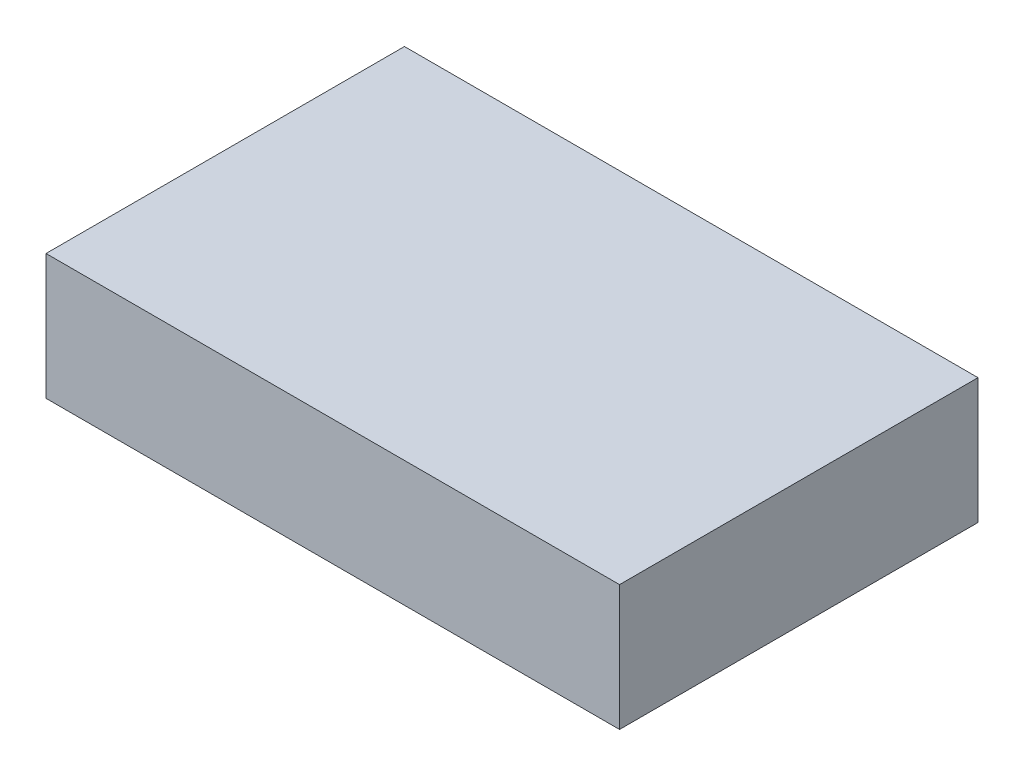
SolidWorks part; units mm, degrees
ref_plane "Front Plane" through (0, 0, 0) normal (0, 0, 1) x (1, 0, 0)
ref_plane "Top Plane" through (0, 0, 0) normal (0, 1, 0) x (1, 0, 0)
ref_plane "Right Plane" through (0, 0, 0) normal (1, 0, 0) x (0, 0, -1)
sketch "Sketch1" plane through (0, 0, 0) normal (0, 1, 0) x (1, 0, 0)
  line L1 (-203.2, 127) -> (203.2, 127)
  line L2 (-203.2, 127) -> (-203.2, -127)
  line L3 (-203.2, -127) -> (203.2, -127)
  line L4 (203.2, 127) -> (203.2, -127)
  line L5 (-203.2, 127) -> (203.2, -127) construction
  line L6 (-203.2, -127) -> (203.2, 127) construction
  point P0 (0, 0)
  dimension "D1" = 254
  dimension "D2" = 406.4
extrude "Boss-Extrude1" add sketch "Sketch1" along normal blind 88.9
